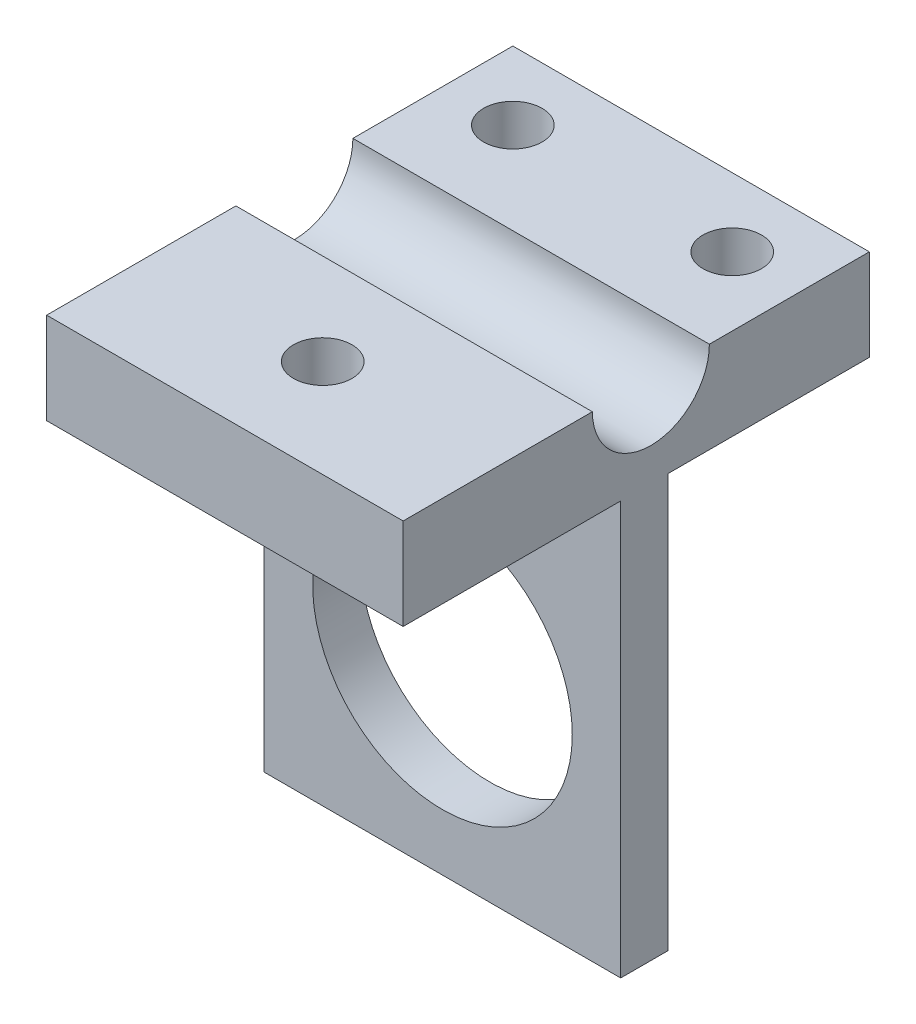
SolidWorks part; units mm, degrees
ref_plane "Front Plane" through (0, 0, 0) normal (0, 0, 1) x (1, 0, 0)
ref_plane "Top Plane" through (0, 0, 0) normal (0, 1, 0) x (1, 0, 0)
ref_plane "Right Plane" through (0, 0, 0) normal (1, 0, 0) x (0, 0, -1)
sketch "Sketch11" plane through (0, 0, 0) normal (0, 1, 0) x (1, 0, 0)
  line L0 (12.3825, 0) -> (12.3825, 6.7945) construction
  line L1 (0, 0) -> (24.765, 0)
  line L2 (0, 0) -> (0, 32.385)
  line L3 (0, 32.385) -> (24.765, 32.385)
  line L4 (24.765, 0) -> (24.765, 32.385)
  line L5 (0, 32.385) -> (2.7305, 32.385) construction
  line L6 (0, 32.385) -> (0, 27.6053) construction
  line L9 (24.765, 32.385) -> (22.0345, 32.385) construction
  line L10 (24.765, 32.385) -> (24.765, 29.6545) construction
  line L13 (12.3825, 6.7945) -> (12.3825, 27.6225) construction
  line L14 (12.3825, 27.6225) -> (4.7625, 27.6225) construction
  line L15 (12.3825, 27.6225) -> (20.0025, 27.6225) construction
  circle A0 centre (4.7625, 27.6225) radius 2.032
  circle A1 centre (20.0025, 27.6225) radius 2.032
  circle A2 centre (12.3825, 6.7945) radius 2.032
  dimension "D5" = 4.064
  dimension "D8" = 4.064
  dimension "D10" = 4.064
  dimension "D2" = 4.7625
  dimension "D3" = 4.7625
  dimension "D9" = 6.7945
  dimension "D11" = 20.828
  dimension "D12" = 7.62
  dimension "D13" = 7.62
extrude "Boss-Extrude1" add sketch "Sketch11" along normal blind 6.35
sketch "Sketch12" plane through (0, 6.35, 0) normal (0, 1, 0) x (1, 0, 0)
  line L0 (12.3825, 0) -> (12.3825, 13.1445) construction
  line L1 (0, 0) -> (24.765, 0) construction
  line L2 (0, 32.385) -> (0, 0) construction
  line L3 (0, 13.1445) -> (24.765, 13.1445)
  line L4 (0, 13.1445) -> (0, 17.2085)
  line L5 (0, 17.2085) -> (24.765, 17.2085)
  line L6 (24.765, 13.1445) -> (24.765, 17.2085)
  line L7 (24.765, 0) -> (24.765, 32.385) construction
  dimension "D1" = 13.1445
  dimension "D2" = 4.064
revolve "Cut-Revolve1" cut sketch "Sketch12" angle 360 about L5
sketch "Sketch14" plane through (0, 0, 0) normal (0, -1, 0) x (1, 0, 0)
  line L0 (12.3825, -32.385) -> (12.3825, -18.415) construction
  line L1 (24.765, -32.385) -> (0, -32.385) construction
  line L2 (24.765, 0) -> (24.765, -32.385) construction
  line L3 (24.765, -18.415) -> (0, -18.415)
  line L4 (24.765, -18.415) -> (24.765, -15.113)
  line L5 (24.765, -15.113) -> (0, -15.113)
  line L6 (0, -18.415) -> (0, -15.113)
  line L8 (0, -32.385) -> (0, 0) construction
  point P12 (12.3825, -18.415)
  dimension "D1" = 13.97
  dimension "D2" = 3.302
extrude "Boss-Extrude2" add sketch "Sketch14" along normal blind 28.702
sketch "Sketch15" plane through (0, 0, -15.113) normal (0, 0, 1) x (1, 0, 0)
  line L0 (12.3825, -28.702) -> (12.3825, -15.748) construction
  line L1 (24.765, -28.702) -> (0, -28.702) construction
  circle A0 centre (12.3825, -15.748) radius 9.017
  dimension "D2" = 18.034
  dimension "D1" = 12.954
extrude "Cut-Extrude1" cut sketch "Sketch15" against normal up to next
